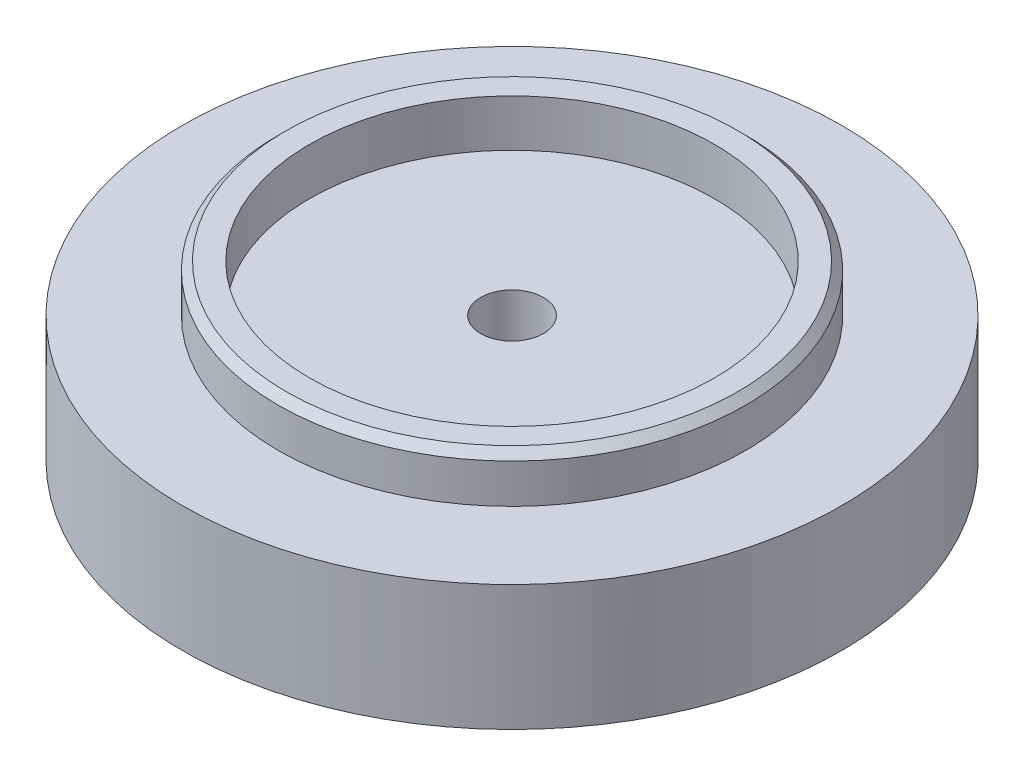
SolidWorks part; units mm, degrees
ref_plane "Płaszczyzna przednia" through (0, 0, 0) normal (0, 0, 1) x (1, 0, 0)
ref_plane "Płaszczyzna górna" through (0, 0, 0) normal (0, 1, 0) x (1, 0, 0)
ref_plane "Płaszczyzna prawa" through (0, 0, 0) normal (1, 0, 0) x (0, 0, -1)
sketch "Sketch1" plane through (0, 0, 0) normal (0, 1, 0) x (1, 0, 0)
  circle A0 centre (0, 0) radius 21
  circle A1 centre (0, 0) radius 2
  dimension "D1" = 42
  dimension "D2" = 4
extrude "Boss-Extrude1" add sketch "Sketch1" along normal blind 4
sketch "Sketch2" plane through (0, 4, 0) normal (0, 1, 0) x (1, 0, 0)
  circle A0 centre (0, 0) radius 14.9
  circle A1 centre (0, 0) radius 2 construction
  circle A2 centre (0, 0) radius 2
  circle A3 centre (0, 0) radius 12.9
  dimension "D1" = 29.8
  dimension "D2" = 2
extrude "Boss-Extrude2" add sketch "Sketch2" along normal blind 3 contours A0 A3
chamfer "Chamfer1" distance 0.5 angle 45 1 edges at (0, 7, 14.9)
sketch "Sketch3" plane through (0, 0, 0) normal (0, -1, 0) x (1, 0, 0)
  circle A0 centre (0, 0) radius 2.65
  circle A1 centre (0, 0) radius 21
  circle A2 centre (0, 0) radius 21
  dimension "D2" = 5.3
  dimension "D1" = 0
extrude "Boss-Extrude3" add sketch "Sketch3" along normal blind 4
sketch "Sketch4" plane through (0, 0, 0) normal (0, -1, 0) x (1, 0, 0)
  circle A0 centre (0, 0) radius 2.65 construction
  circle A1 centre (0, 0) radius 2 construction
  circle A2 centre (0, 0) radius 2.65
  circle A3 centre (0, 0) radius 2
extrude "Boss-Extrude4" add sketch "Sketch4" along normal blind 2
chamfer "Chamfer2" distance 0.5 angle 45 1 edges at (0, -4, -2.65)
